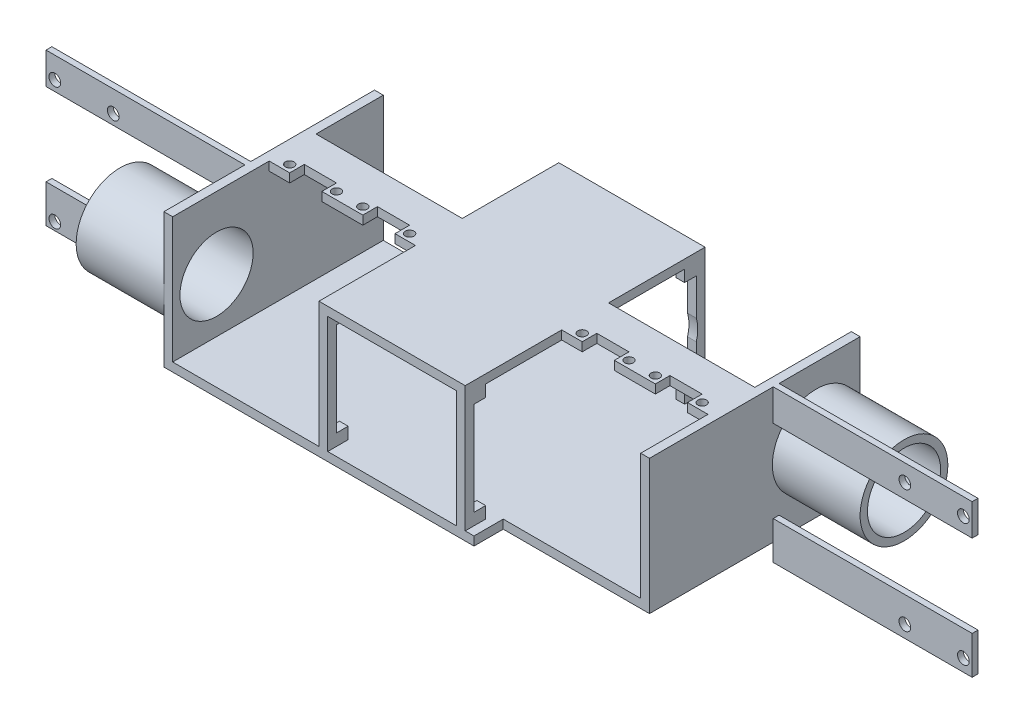
SolidWorks part; units mm, degrees
material "ABS PC"
ref_plane "Front Plane" through (0, 0, 0) normal (0, 0, 1) x (1, 0, 0)
ref_plane "Top Plane" through (0, 0, 0) normal (0, 1, 0) x (1, 0, 0)
ref_plane "Right Plane" through (0, 0, 0) normal (1, 0, 0) x (0, 0, -1)
sketch "Sketch1" plane through (0, 0, 0) normal (0, 0, 1) x (1, 0, 0)
  line L1 (-25, -23) -> (25, -23)
  line L2 (-25, -23) -> (-25, 23)
  line L3 (-25, 23) -> (25, 23)
  line L4 (25, -23) -> (25, 23)
  line L5 (-25, -23) -> (25, 23) construction
  line L6 (-25, 23) -> (25, -23) construction
  point P0 (0, 0)
  dimension "D1" = 50
  dimension "D2" = 46
extrude "Boss-Extrude1" add sketch "Sketch1" along normal mid plane 82
sketch "Sketch2" plane through (0, 0, 41) normal (0, 0, 1) x (1, 0, 0)
  line L0 (25, 23) -> (-25, 23) construction
  line L1 (-22, 20) -> (22, 20)
  line L2 (-22, 20) -> (-22, -20)
  line L3 (-22, -20) -> (22, -20)
  line L4 (22, 20) -> (22, -20)
  line L5 (-22, 20) -> (22, -20) construction
  line L6 (-22, -20) -> (22, 20) construction
  line L7 (-25, 23) -> (-25, -23) construction
  point P0 (0, 0)
  dimension "D1" = 3
  dimension "D2" = 3
extrude "Cut-Extrude1" cut sketch "Sketch2" against normal up to next
sketch "Sketch3" plane through (-25, 0, 0) normal (-1, 0, 0) x (0, 0, 1)
  line L0 (-34, 16) -> (-34, 20)
  line L1 (-34, 20) -> (34, 20)
  line L2 (34, 20) -> (34, 16)
  line L3 (34, 16) -> (38, 16)
  line L4 (38, 16) -> (38, -16)
  line L5 (38, -16) -> (34, -16)
  line L6 (34, -16) -> (34, -20)
  line L7 (34, -20) -> (-34, -20)
  line L8 (-34, -20) -> (-34, -16)
  line L9 (-34, -16) -> (-38, -16)
  line L10 (-38, -16) -> (-38, 16)
  line L11 (-38, 16) -> (-34, 16)
  line L12 (41, 23) -> (-41, 23) construction
  line L13 (-41, 23) -> (-41, -23) construction
  line L14 (41, 23) -> (41, -23) construction
  line L15 (41, -23) -> (-41, -23) construction
  dimension "D1" = 3
  dimension "D2" = 3
  dimension "D3" = 3
  dimension "D4" = 3
  dimension "D5" = 7
  dimension "D6" = 7
  dimension "D7" = 7
  dimension "D8" = 7
  dimension "D9" = 7
  dimension "D10" = 7
  dimension "D11" = 7
  dimension "D12" = 7
extrude "Cut-Extrude2" cut sketch "Sketch3" against normal through all both and the other way through all
sketch "Sketch4" plane through (25, 0, 0) normal (1, 0, 0) x (0, 0, -1)
  line L0 (41, -23) -> (41, 23) construction
  line L1 (-41, -23) -> (41, -23)
  line L2 (-41, -23) -> (-41, -20)
  line L3 (-41, -20) -> (41, -20)
  line L4 (41, -23) -> (41, -20)
  dimension "D1" = 3
extrude "Boss-Extrude2" add sketch "Sketch4" along normal blind 50
sketch "Sketch7" plane through (25, 0, 0) normal (1, 0, 0) x (0, 0, -1)
  line L0 (-41, 23) -> (41, 23) construction
  line L1 (-8, 23) -> (8, 23)
  line L2 (-8, 23) -> (-8, 20)
  line L3 (-8, 20) -> (8, 20)
  line L4 (8, 23) -> (8, 20)
  line L5 (-34, 20) -> (34, 20) construction
  line L7 (-41, -20) -> (-41, 23) construction
  dimension "D1" = 16
  dimension "D2" = 33
extrude "Boss-Extrude4" add sketch "Sketch7" along normal blind 50
sketch "Sketch8" plane through (75, 0, 0) normal (1, 0, 0) x (0, 0, -1)
  line L1 (-41, -23) -> (41, -23)
  line L2 (-41, -23) -> (-41, 23)
  line L3 (-41, 23) -> (41, 23)
  line L4 (41, -23) -> (41, 23)
  dimension "D1" = 46
  dimension "D2" = 82
extrude "Boss-Extrude5" add sketch "Sketch8" along normal blind 3
sketch "Sketch9" plane through (0, 23, 0) normal (0, 1, 0) x (1, 0, 0)
  line L0 (68, -8) -> (68, -3)
  line L1 (75, -8) -> (25, -8) construction
  line L2 (68, -3) -> (57, -3)
  line L3 (57, -3) -> (57, -8)
  line L4 (75, -8) -> (75, -41) construction
  dimension "D1" = 7
  dimension "D2" = 18
  dimension "D3" = 5
extrude "Cut-Extrude4" cut sketch "Sketch9" against normal blind 3 and the other way through all
sketch "Sketch10" plane through (0, 23, 0) normal (0, 1, 0) x (1, 0, 0)
  line L0 (32, -8) -> (32, -3)
  line L1 (57, -8) -> (25, -8) construction
  line L2 (32, -3) -> (43, -3)
  line L3 (43, -3) -> (43, -8)
  line L4 (43, -8) -> (32, -8)
  line L5 (25, -41) -> (25, -8) construction
  dimension "D1" = 5
  dimension "D2" = 11
  dimension "D3" = 7
extrude "Cut-Extrude5" cut sketch "Sketch10" against normal up to next
sketch "Sketch11" plane through (0, 23, 0) normal (0, 1, 0) x (1, 0, 0)
  line L0 (75, -8) -> (68, -8) construction
  line L1 (68, -3) -> (68, -8) construction
  line L2 (57, -8) -> (57, -3) construction
  line L3 (57, -8) -> (43, -8) construction
  line L4 (43, -8) -> (43, -3) construction
  line L5 (32, -8) -> (25, -8) construction
  line L6 (32, -3) -> (32, -8) construction
  circle A0 centre (29.5, -5.5) radius 1.5
  circle A1 centre (45.5, -5.5) radius 1.5
  circle A2 centre (54.5, -5.5) radius 1.5
  circle A3 centre (70.5, -5.5) radius 1.5
  dimension "D1" = 3
  dimension "D2" = 3
  dimension "D3" = 3
  dimension "D4" = 3
  dimension "D5" = 2.5
  dimension "D6" = 2.5
  dimension "D7" = 2.5
  dimension "D8" = 2.5
  dimension "D9" = 2.5
  dimension "D10" = 2.5
  dimension "D11" = 2.5
  dimension "D12" = 2.5
extrude "Cut-Extrude6" cut sketch "Sketch11" against normal up to next
sketch "Sketch12" plane through (78, 0, 0) normal (1, 0, 0) x (0, 0, -1)
  line L0 (41, -23) -> (41, 23) construction
  circle A0 centre (26, 0) radius 15
  dimension "D1" = 30
  dimension "D2" = 15
extrude "Boss-Extrude6" add sketch "Sketch12" along normal blind 30
sketch "Sketch13" plane through (108, 0, 0) normal (1, 0, 0) x (0, 0, -1)
  line L0 (41, -23) -> (41, 0) construction
  circle A0 centre (26, 0) radius 12.5
  dimension "D1" = 25
  dimension "D2" = 15
extrude "Cut-Extrude7" cut sketch "Sketch13" against normal through all
sketch "Sketch14" plane through (78, 0, 0) normal (1, 0, 0) x (0, 0, -1)
  line L0 (41, 23) -> (-41, 23) construction
  line L1 (11.3, 23) -> (13.3, 23)
  line L2 (11.3, 23) -> (11.3, 12.2)
  line L3 (11.3, 12.2) -> (13.3, 12.2)
  line L4 (13.3, 23) -> (13.3, 12.2)
  line L11 (-41, 23) -> (-41, -23) construction
  line L12 (11.3, -16) -> (13.3, -16)
  line L13 (11.3, -16) -> (11.3, -29)
  line L14 (11.3, -29) -> (13.3, -29)
  line L15 (13.3, -16) -> (13.3, -29)
  line L16 (-41, -23) -> (41, -23) construction
  dimension "D1" = 10.8
  dimension "D2" = 52.3
  dimension "D3" = 2
  dimension "D4" = 13
  dimension "D5" = 54.3
  dimension "D6" = 2
  dimension "D7" = 7
extrude "Boss-Extrude7" add sketch "Sketch14" along normal blind 68
sketch "Sketch15" plane through (0, 0, -13.3) normal (0, 0, -1) x (-1, 0, 0)
  line L1 (-78, 23) -> (-78, 12.2) construction
  line L2 (-78, -16) -> (-78, -23) construction
  line L4 (-146, 12.2) -> (-78, 12.2) construction
  circle A0 centre (-143, -24.8) radius 2
  circle A1 centre (-123, -24.8) radius 2
  circle A2 centre (-123, 17.2) radius 2
  circle A3 centre (-143, 17.2) radius 2
  dimension "D1" = 4
  dimension "D2" = 4
  dimension "D3" = 4
  dimension "D4" = 4
  dimension "D5" = 45
  dimension "D6" = 45
  dimension "D7" = 20
  dimension "D8" = 20
  dimension "D9" = 5
  dimension "D10" = 42
  dimension "D11" = 5
  dimension "D12" = 42
mirror "Mirror1" about plane through (0, 0, 0) normal (1, 0, 0) of "Cut-Extrude6", "Cut-Extrude5", "Boss-Extrude5", "Boss-Extrude2", "Boss-Extrude4", "Cut-Extrude4"
sketch "Sketch16" plane through (-78, 0, 0) normal (-1, 0, 0) x (0, 0, 1)
  line L0 (41, 23) -> (41, -23) construction
  circle A0 centre (26, -1.5051) radius 15
  dimension "D1" = 30
  dimension "D2" = 15
extrude "Boss-Extrude8" add sketch "Sketch16" along normal blind 30
sketch "Sketch17" plane through (-108, 0, 0) normal (-1, 0, 0) x (0, 0, 1)
  circle A0 centre (26, -1.5051) radius 12.5
  dimension "D1" = 25
extrude "Cut-Extrude9" cut sketch "Sketch17" against normal up to next
sketch "Sketch18" plane through (-78, 0, 0) normal (-1, 0, 0) x (0, 0, 1)
  line L1 (11.3, 12.2) -> (13.3, 12.2)
  line L2 (11.3, 12.2) -> (11.3, 23)
  line L3 (11.3, 23) -> (13.3, 23)
  line L4 (13.3, 12.2) -> (13.3, 23)
  line L5 (-41, -23) -> (-41, 23) construction
  line L6 (-41, 23) -> (41, 23) construction
  dimension "D1" = 10.8
  dimension "D2" = 54.3
  dimension "D3" = 2
  dimension "D4" = 0
extrude "Boss-Extrude9" add sketch "Sketch18" along normal blind 68
sketch "Sketch19" plane through (-78, 0, 0) normal (-1, 0, 0) x (0, 0, 1)
  line L0 (41, -23) -> (-41, -23) construction
  line L1 (11.3, -29) -> (13.3, -29)
  line L2 (11.3, -29) -> (11.3, -16)
  line L3 (11.3, -16) -> (13.3, -16)
  line L4 (13.3, -29) -> (13.3, -16)
  line L5 (-41, -23) -> (-41, 23) construction
  dimension "D1" = 13
  dimension "D2" = 7
  dimension "D3" = 54.3
  dimension "D4" = 2
extrude "Boss-Extrude10" add sketch "Sketch19" along normal blind 68
sketch "Sketch20" plane through (0, 0, 13.3) normal (0, 0, 1) x (1, 0, 0)
  line L0 (-78, 12.2) -> (-78, 23) construction
  line L1 (-146, 12.2) -> (-78, 12.2) construction
  line L2 (-146, -29) -> (-78, -29) construction
  circle A0 centre (-123, 15.6949) radius 2
  circle A1 centre (-143, 15.6949) radius 2
  circle A2 centre (-123, -26.3051) radius 2
  circle A3 centre (-143, -26.3051) radius 2
  dimension "D5" = 4
  dimension "D6" = 4
  dimension "D7" = 4
  dimension "D8" = 4
  dimension "D1" = 20
  dimension "D2" = 20
  dimension "D3" = 42
  dimension "D4" = 42
  dimension "D9" = 45
  dimension "D10" = 3.4949
  dimension "D11" = 2.6949
  dimension "D12" = 3.4949
extrude "Cut-Extrude10" cut sketch "Sketch15" against normal up to next
extrude "Cut-Extrude11" cut sketch "Sketch20" against normal up to next
sketch "Sketch21" plane through (0, -23, 0) normal (0, -1, 0) x (1, 0, 0)
  line L1 (-78, -41) -> (-28, -41)
  line L2 (-78, -41) -> (-78, -31)
  line L3 (-78, -31) -> (-28, -31)
  line L4 (-28, -41) -> (-28, -31)
  dimension "D1" = 10
  dimension "D2" = 50
extrude "Cut-Extrude12" cut sketch "Sketch21" against normal up to next
sketch "Sketch22" plane through (0, -23, 0) normal (0, -1, 0) x (-1, 0, 0)
  line L1 (-78, -41) -> (-28, -41)
  line L2 (-78, -41) -> (-78, -31)
  line L3 (-78, -31) -> (-28, -31)
  line L4 (-28, -41) -> (-28, -31)
  dimension "D1" = 10
  dimension "D2" = 50
extrude "Cut-Extrude13" cut sketch "Sketch22" against normal up to next
